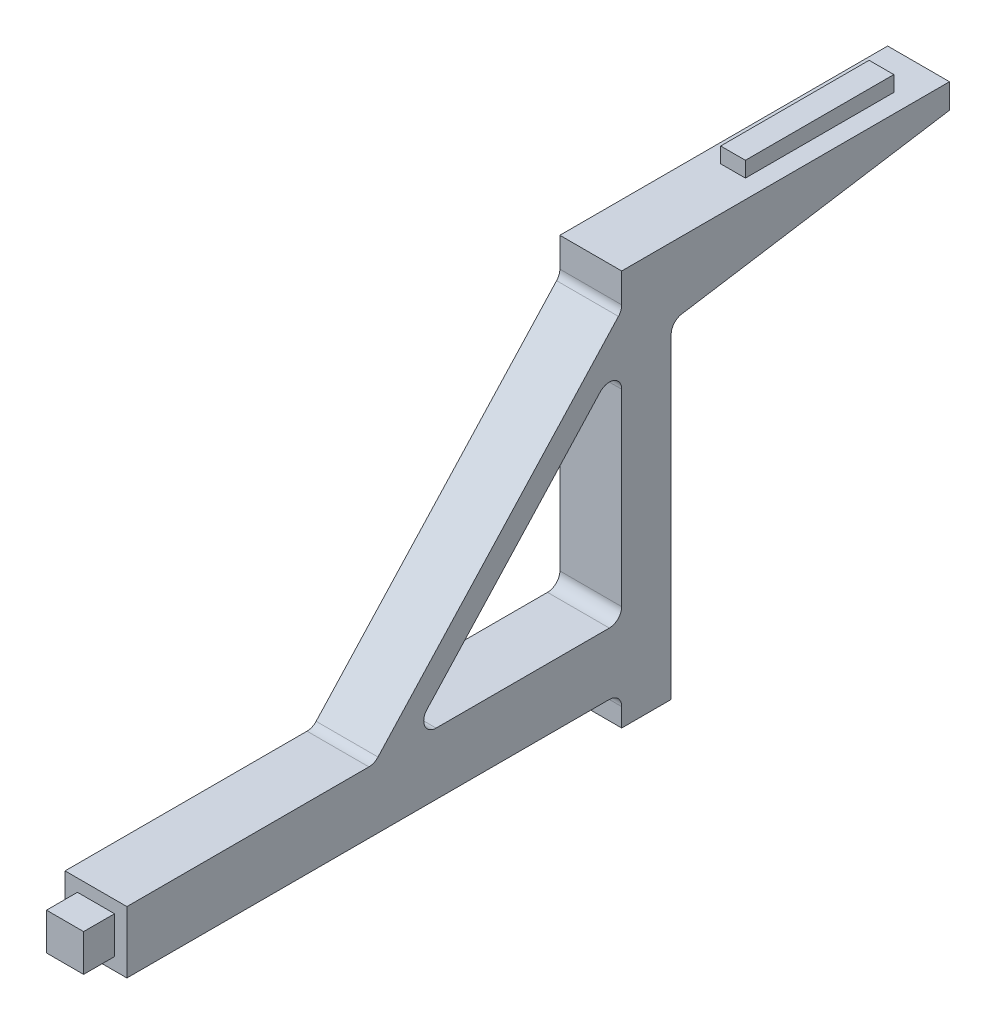
SolidWorks part; units mm, degrees
ref_plane "Front Plane" through (0, 0, 0) normal (0, 0, 1) x (1, 0, 0)
ref_plane "Top Plane" through (0, 0, 0) normal (0, 1, 0) x (1, 0, 0)
ref_plane "Right Plane" through (0, 0, 0) normal (1, 0, 0) x (0, 0, -1)
sketch "Sketch1" plane through (0, 0, 0) normal (0, 0, 1) x (1, 0, 0)
  line L0 (0, 0) -> (0, 127) construction
  line L1 (-6.35, 12.7) -> (-6.35, 10.9985)
  line L2 (-19.0544, 12.7) -> (13.0348, 12.7) construction
  line L3 (6.35, 43.18) -> (6.35, 10.9985)
  line L5 (-6.35, 12.7) -> (-6.35, 93.98)
  line L6 (-6.35, 93.98) -> (6.35, 93.98)
  line L7 (6.35, 43.18) -> (6.35, 93.98)
  circle A0 centre (0, 0) radius 5.08
  arc A1 (-6.35, 10.9985) -> (6.35, 10.9985) centre (0, 0) ccw
  circle A2 centre (0, 8.128) radius 1.778
  circle A3 centre (8.128, 0) radius 1.778
  circle A4 centre (0, -8.128) radius 1.778
  circle A5 centre (-8.128, 0) radius 1.778
  point P15 (0, 0)
  dimension "D1" = 10.16
  dimension "D2" = 25.4
  dimension "D4" = 3.556
  dimension "D3" = 8.128
  dimension "D6" = 12.7
  dimension "D7" = 81.28
  dimension "D8" = 1.7015
  dimension "D5" = 4
extrude "Boss-Extrude1" add sketch "Sketch1" along normal blind 10.16
sketch "Sketch3" plane through (0, 0, 10.16) normal (0, 0, 1) x (1, 0, 0)
  line L0 (0, 0) -> (0, 25.4) construction
  line L2 (-6.35, 19.05) -> (6.35, 19.05)
  line L3 (-6.35, 19.05) -> (-6.35, 31.75)
  line L4 (-6.35, 31.75) -> (6.35, 31.75)
  line L5 (6.35, 19.05) -> (6.35, 31.75)
  line L6 (-6.35, 19.05) -> (6.35, 31.75) construction
  line L7 (-6.35, 31.75) -> (6.35, 19.05) construction
  dimension "D1" = 12.7
  dimension "D2" = 12.7
  dimension "D3" = 25.4
extrude "Boss-Extrude2" add sketch "Sketch3" along normal blind 101.6
sketch "Sketch5" plane through (-6.35, 0, 0) normal (-1, 0, 0) x (0, 0, 1)
  line L6 (31.75, 63.5) -> (60.96, 31.75)
  line L7 (54.0572, 31.75) -> (60.96, 31.75)
  line L10 (49.3836, 36.83) -> (29.5208, 58.42)
  line L13 (111.76, 31.75) -> (10.16, 31.75) construction
  line L14 (29.5208, 58.42) -> (10.16, 79.4643)
  line L15 (10.16, 93.98) -> (10.16, 31.75) construction
  line L16 (31.75, 63.5) -> (10.16, 86.9674)
  line L17 (10.16, 86.9674) -> (10.16, 79.4643)
  line L18 (49.3836, 36.83) -> (54.0572, 31.75)
  dimension "D4" = 5.08
sketch "Sketch6" plane through (0, 0, 111.76) normal (0, 0, 1) x (1, 0, 0)
  line L0 (-6.35, 19.05) -> (6.35, 19.05) construction
  line L1 (-3.81, 21.59) -> (3.81, 21.59)
  line L2 (-3.81, 21.59) -> (-3.81, 29.21)
  line L3 (-3.81, 29.21) -> (3.81, 29.21)
  line L4 (3.81, 21.59) -> (3.81, 29.21)
  line L5 (-3.81, 21.59) -> (3.81, 29.21) construction
  line L6 (-3.81, 29.21) -> (3.81, 21.59) construction
  line L7 (-6.35, 31.75) -> (-6.35, 19.05) construction
  point P0 (0, 25.4)
  point P5 (0, 25.4)
  dimension "D1" = 7.62
  dimension "D2" = 7.62
  dimension "D3" = 6.35
  dimension "D4" = 6.35
extrude "Boss-Extrude3" add sketch "Sketch6" along normal blind 6.35
extrude "Boss-Extrude4" add sketch "Sketch5" along normal up to surface (12.7 mm away) from surface at -12.7 up to face at (-6.35, 38.9446, 33.02) starting at face at (6.35, 38.9446, 33.02)
fillet "Fillet2" radius 2.54 1 edges at (0, 31.75, 60.96)
sketch "Sketch7" plane through (6.35, 0, 0) normal (1, 0, 0) x (0, 0, -1)
  line L0 (0, 93.98) -> (0, 88.9)
  line L1 (0, 10.9985) -> (0, 93.98) construction
  line L2 (0, 93.98) -> (57.15, 93.98)
  line L6 (57.15, 93.98) -> (57.15, 88.9)
  line L8 (57.15, 88.9) -> (0, 88.9)
  dimension "D1" = 5.08
  dimension "D2" = 57.15
extrude "Boss-Extrude5" add sketch "Sketch7" along direction (-1, 0, 0) on the side of the normal up to surface (12.7 mm away) from surface at -12.7 starting at face at (-6.35, 47.6548, 24.7924)
sketch "Sketch9" plane through (0, 0, 111.76) normal (0, 0, 1) x (1, 0, 0)
  line L1 (12.7, -12.7) -> (-12.7, -12.7)
  line L2 (12.7, -12.7) -> (12.7, 12.7)
  line L3 (12.7, 12.7) -> (-12.7, 12.7)
  line L4 (-12.7, -12.7) -> (-12.7, 12.7)
  dimension "D1" = 25.4
  dimension "D2" = 25.4
extrude "Cut-Extrude1" cut sketch "Sketch9" against normal up to surface (111.76 mm away) up to face at (1.778, 8.128, 0)
sketch "Sketch11" plane through (6.35, 0, 0) normal (1, 0, 0) x (0, 0, -1)
  line L0 (57.15, 88.9) -> (57.15, 77.275) construction
  line L1 (57.15, 77.275) -> (0, 77.275) construction
  line L2 (0, 12.7) -> (0, 88.9) construction
  line L3 (0, 79.815) -> (57.15, 88.9)
  line L4 (57.15, 88.9) -> (0, 88.9)
  line L5 (0, 79.815) -> (0, 88.9)
  dimension "D1" = 11.625
  dimension "D2" = 2.54
extrude "Boss-Extrude6" add sketch "Sketch11" against normal up to surface (12.7 mm away) up to face at (-6.35, 51.0085, 22.6712)
fillet "Fillet3" radius 2.54 6 edges at (0, 79.4643, 10.16) (0, 86.9674, 10.16) (0, 19.05, 10.16) (0, 31.75, 54.0572) (0, 31.75, 10.16) (0, 79.815, 0)
sketch "Sketch12" plane through (0, 93.98, 0) normal (0, 1, 0) x (1, 0, 0)
  line L0 (6.35, -10.16) -> (6.35, 57.15) construction
  line L1 (-2.54, 19.05) -> (2.54, 19.05)
  line L2 (-2.54, 19.05) -> (-2.54, 49.53)
  line L3 (-2.54, 49.53) -> (2.54, 49.53)
  line L4 (2.54, 19.05) -> (2.54, 49.53)
  line L5 (-2.54, 19.05) -> (2.54, 49.53) construction
  line L6 (-2.54, 49.53) -> (2.54, 19.05) construction
  line L7 (6.35, 57.15) -> (-6.35, 57.15) construction
  point P0 (0, 34.29)
  dimension "D1" = 5.08
  dimension "D2" = 30.48
  dimension "D3" = 3.81
  dimension "D4" = 7.62
extrude "Boss-Extrude7" add sketch "Sketch12" along normal blind 3.175
sketch "Sketch13" plane through (0, 12.7, 0) normal (0, -1, 0) x (1, 0, 0)
  line L1 (-3.937, 1.143) -> (3.937, 1.143)
  line L2 (-3.937, 1.143) -> (-3.937, 9.017)
  line L3 (-3.937, 9.017) -> (3.937, 9.017)
  line L4 (3.937, 1.143) -> (3.937, 9.017)
  line L5 (-3.937, 1.143) -> (3.937, 9.017) construction
  line L6 (-3.937, 9.017) -> (3.937, 1.143) construction
  line L7 (-6.35, 10.16) -> (-6.35, 0) construction
  line L8 (-6.35, 0) -> (6.35, 0) construction
  point P0 (0, 5.08)
  dimension "D1" = 7.874
  dimension "D2" = 7.874
  dimension "D3" = 2.413
  dimension "D4" = 1.143
extrude "Cut-Extrude3" cut sketch "Sketch13" against normal blind 6.35
